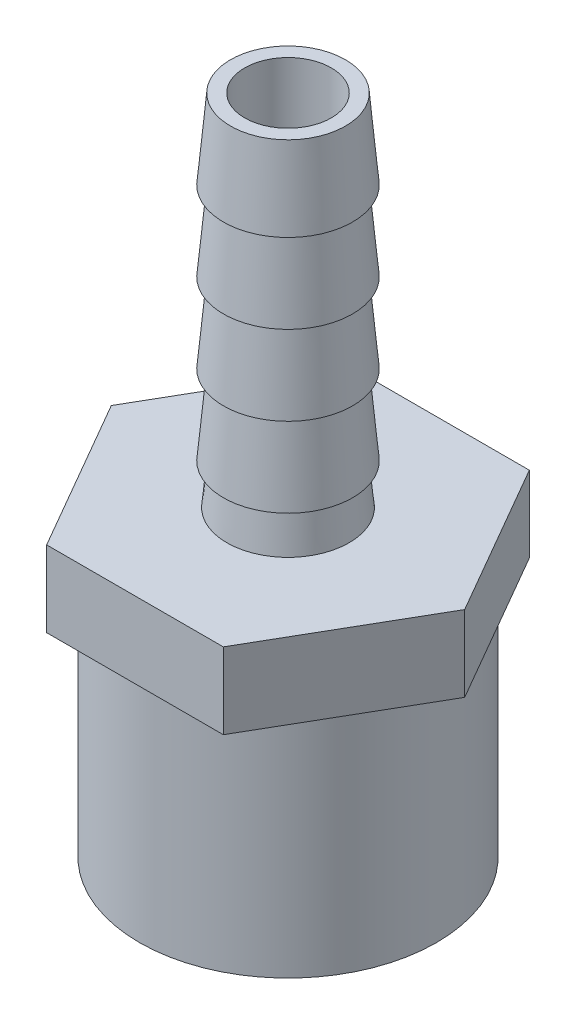
SolidWorks part; units mm, degrees
ref_plane "Front Plane" through (0, 0, 0) normal (0, 0, 1) x (1, 0, 0)
ref_plane "Top Plane" through (0, 0, 0) normal (0, 1, 0) x (1, 0, 0)
ref_plane "Right Plane" through (0, 0, 0) normal (1, 0, 0) x (0, 0, -1)
other "Default"
sketch "Sketch1" plane through (0, 0, 0) normal (0, 1, 0) x (1, 0, 0)
  line L1 (9.9882, 0) -> (4.9941, 8.65)
  line L2 (4.9941, 8.65) -> (-4.9941, 8.65)
  line L3 (-4.9941, 8.65) -> (-9.9882, 0)
  line L4 (-9.9882, 0) -> (-4.9941, -8.65)
  line L5 (-4.9941, -8.65) -> (4.9941, -8.65)
  line L6 (4.9941, -8.65) -> (9.9882, 0)
  circle A0 centre (0, 0) radius 8.65 construction
  circle A1 centre (0, 0) radius 2.45
  dimension "D2" = 4.9
  dimension "Hex Diameter" = 17.3
extrude "Boss-Extrude1" add sketch "Sketch1" against normal blind 4.3
sketch "Sketch2" plane through (0, 0, 0) normal (0, 0, 1) x (1, 0, 0)
  line L0 (2.45, 0) -> (2.45, 20.3)
  line L1 (-4.9941, 0) -> (4.9941, 0) construction
  line L2 (2.45, 20.3) -> (3.25, 20.3)
  line L3 (3.25, 20.3) -> (3.65, 15.8)
  line L4 (3.65, 15.8) -> (3.25, 15.8)
  line L5 (3.25, 15.8) -> (3.65, 11.3)
  line L6 (3.65, 11.3) -> (3.25, 11.3)
  line L7 (3.25, 11.3) -> (3.65, 6.8)
  line L8 (3.65, 6.8) -> (3.25, 6.8)
  line L9 (3.25, 6.8) -> (3.65, 2.3)
  line L10 (3.65, 2.3) -> (3.25, 2.3)
  line L11 (3.25, 2.3) -> (3.4544, 0)
  line L12 (3.4544, 0) -> (2.45, 0)
  line L13 (0, -1.9953) -> (0, 5.0004) construction
  dimension "D1" = 4.9
  dimension "D2" = 7.3
  dimension "D3" = 6.5
  dimension "D4" = 4.5
  dimension "D5" = 20.3
revolve "Revolve1" add sketch "Sketch2" angle 360 about L13
sketch "Lower Threads" plane through (0, -4.3, 0) normal (0, -1, 0) x (1, 0, 0)
  circle A0 centre (0, 0) radius 8.4
  circle A1 centre (0, 0) radius 5.55
  dimension "ID" = 11.1
  dimension "OD" = 16.8
extrude "Boss-Extrude2" add sketch "Lower Threads" along normal blind 12.8
